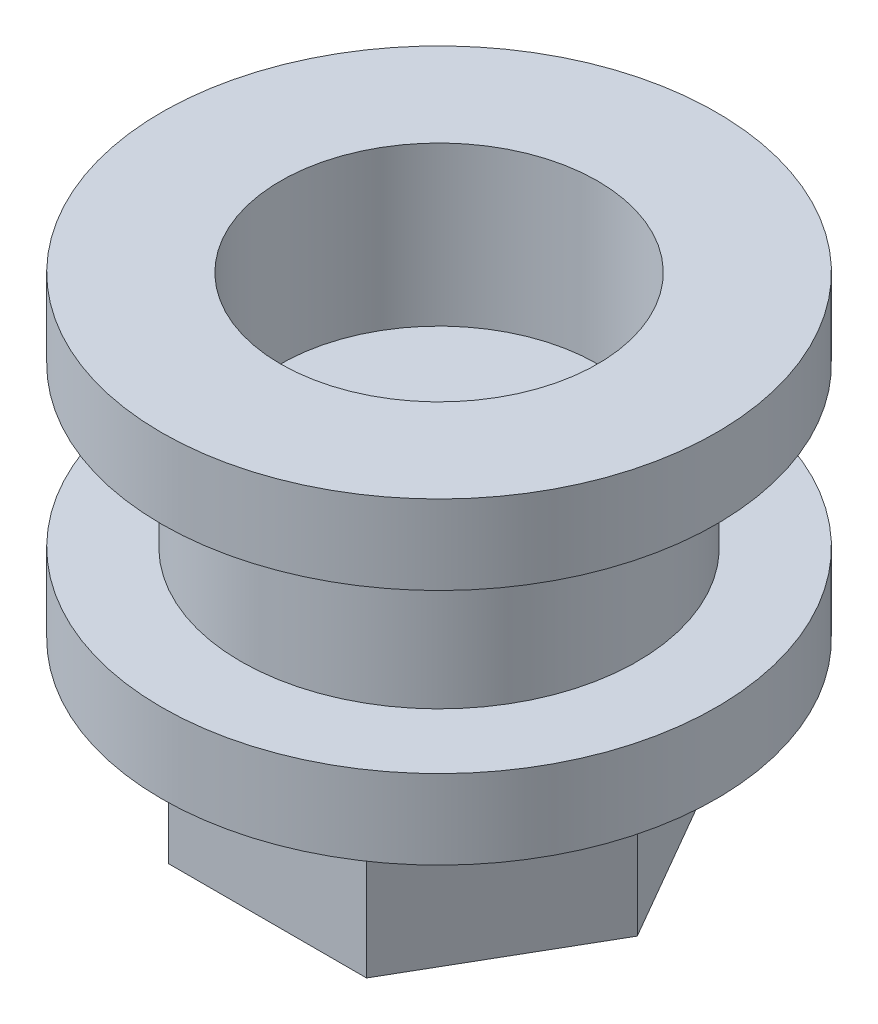
SolidWorks part; units mm, degrees
material "5052-H34"
ref_plane "前视基准面" through (0, 0, 0) normal (0, 0, 1) x (1, 0, 0)
ref_plane "上视基准面" through (0, 0, 0) normal (0, 1, 0) x (1, 0, 0)
ref_plane "右视基准面" through (0, 0, 0) normal (1, 0, 0) x (0, 0, -1)
sketch "草图2" plane through (0, 0, 0) normal (0, 1, 0) x (1, 0, 0)
  line L0 (0, 0) -> (5, 0)
  line L1 (0, 0) -> (2.5, 4.3301)
  line L2 (0, 0) -> (-2.5, 4.3301)
  line L3 (0, 0) -> (-5, 0)
  line L4 (0, 0) -> (-2.5, -4.3301)
  line L5 (0, 0) -> (2.5, -4.3301)
  line L6 (5, 0) -> (2.5, 4.3301)
  line L7 (2.5, 4.3301) -> (-2.5, 4.3301)
  line L8 (-2.5, 4.3301) -> (-5, 0)
  line L9 (-2.5, -4.3301) -> (2.5, -4.3301)
  line L10 (2.5, -4.3301) -> (5, 0)
  line L11 (-2.5, -4.3301) -> (-5, 0)
extrude "凸台-拉伸1" add sketch "草图2" along normal blind 4 contours L2 L8 L3 | L11 L4 L3 | L4 L9 L5 | L5 L10 L0 | L0 L6 L1 | L1 L7 L2
sketch "草图3" plane through (0, 4, 0) normal (0, 1, 0) x (1, 0, 0)
  circle A1 centre (0, 0) radius 7
sketch "草图4" plane through (0, 0, 0) normal (0, -1, 0) x (1, 0, 0)
  circle A0 centre (0, 0) radius 1.5
extrude "切除-拉伸1" cut sketch "草图4" against normal blind 15
extrude "凸台-拉伸4" add sketch "草图3" along normal blind 2
sketch "草图10" plane through (0, 6, 0) normal (0, 1, 0) x (1, 0, 0)
  circle A0 centre (0, 0) radius 5
extrude "凸台-拉伸7" add sketch "草图10" along normal blind 4 contours A0
sketch "草图11" plane through (0, 10, 0) normal (0, 1, 0) x (1, 0, 0)
  circle A0 centre (0, 0) radius 7
extrude "凸台-拉伸8" add sketch "草图11" along normal blind 2
sketch "草图12" plane through (0, 12, 0) normal (0, 1, 0) x (1, 0, 0)
  circle A0 centre (0, 0) radius 4
extrude "切除-拉伸5" cut sketch "草图12" against normal blind 4
